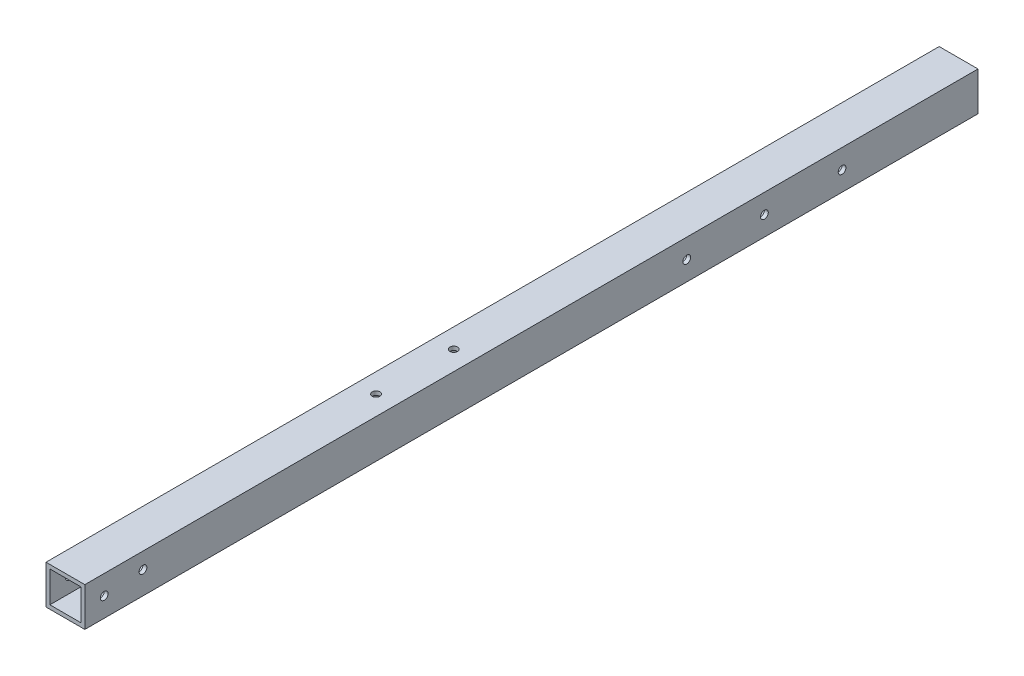
SolidWorks part; units mm, degrees
ref_plane "前视基准面" through (0, 0, 0) normal (0, 0, 1) x (1, 0, 0)
ref_plane "上视基准面" through (0, 0, 0) normal (0, 1, 0) x (1, 0, 0)
ref_plane "右视基准面" through (0, 0, 0) normal (1, 0, 0) x (0, 0, -1)
sketch "草图1" plane through (0, 0, 0) normal (0, 0, 1) x (1, 0, 0)
  line L1 (-10, -10) -> (10, -10)
  line L2 (-10, -10) -> (-10, 10)
  line L3 (-10, 10) -> (10, 10)
  line L4 (10, -10) -> (10, 10)
  line L5 (-10, -10) -> (10, 10) construction
  line L6 (-10, 10) -> (10, -10) construction
  line L7 (-8, 8) -> (8, 8)
  line L8 (-8, 8) -> (-8, -8)
  line L9 (-8, -8) -> (8, -8)
  line L10 (8, 8) -> (8, -8)
  line L11 (-8, 8) -> (8, -8) construction
  line L12 (-8, -8) -> (8, 8) construction
  point P0 (0, 0)
  point P5 (0, 0)
  dimension "D1" = 20
  dimension "D2" = 16
extrude "凸台-拉伸1" add sketch "草图1" along normal blind 460
sketch "草图2" plane through (10, 0, 0) normal (1, 0, 0) x (0, 0, -1)
  line L0 (-1000, 0) -> (49000, 0) construction
  line L2 (-460, -10) -> (-460, 10) construction
  circle A2 centre (-450, 0) radius 2
  circle A4 centre (-70, 0) radius 2
  circle A5 centre (-110, 0) radius 2
  circle A6 centre (-150, 0) radius 2
  circle A8 centre (-37.153, -18.3748) radius 2 construction
  circle A9 centre (-17.2273, -16.6522) radius 2 construction
  circle A11 centre (-37.153, -18.3748) radius 2
  circle A12 centre (-17.2273, -16.6522) radius 2
  circle A13 centre (-430.0743, 1.7226) radius 2 construction
  circle A14 centre (-430.0743, 1.7226) radius 2
  dimension "D5" = 4
  dimension "D7" = 10
extrude "切除-拉伸1" cut sketch "草图2" against normal through all
sketch "草图3" plane through (0, 10, 0) normal (0, 1, 0) x (1, 0, 0)
  line L0 (10, -460) -> (10, 0) construction
  circle A2 centre (0, -260) radius 2
  circle A3 centre (0, -300) radius 2
  dimension "D1" = 40
  dimension "D2" = 10
  dimension "D3" = 10
  dimension "D4" = 260
  dimension "D5" = 4
  dimension "D6" = 4
extrude "切除-拉伸2" cut sketch "草图3" against normal through all
